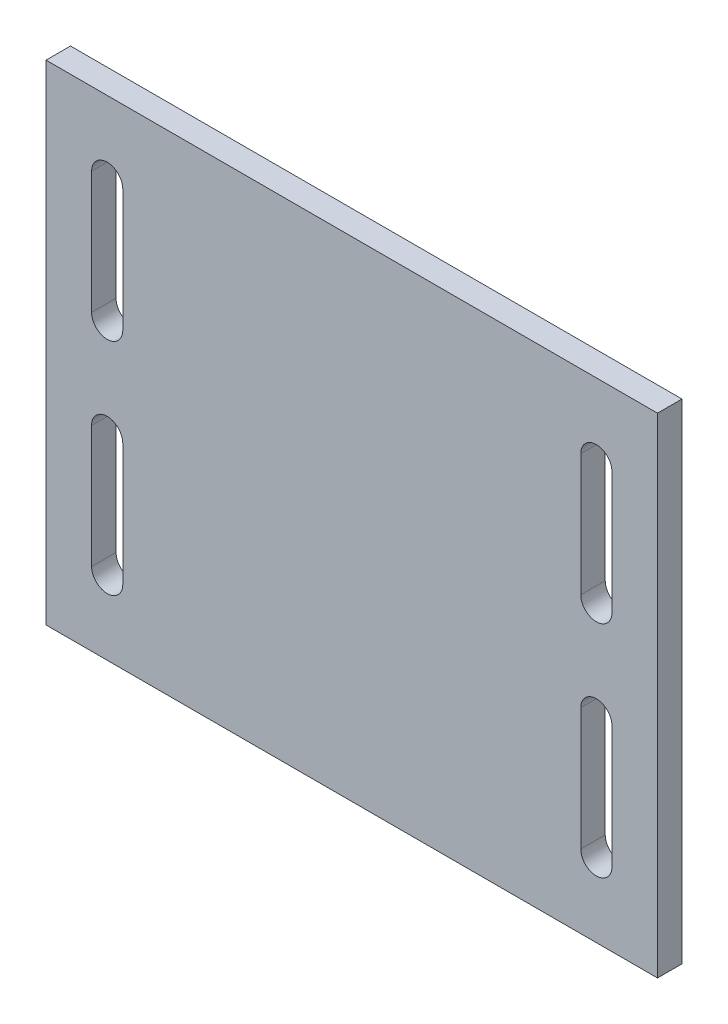
SolidWorks part; units mm, degrees
ref_plane "Front Plane" through (0, 0, 0) normal (0, 0, 1) x (1, 0, 0)
ref_plane "Top Plane" through (0, 0, 0) normal (0, 1, 0) x (1, 0, 0)
ref_plane "Right Plane" through (0, 0, 0) normal (1, 0, 0) x (0, 0, -1)
sketch "Sketch1" plane through (0, 0, 0) normal (0, 0, 1) x (1, 0, 0)
  line L0 (10, 68) -> (10, 48) construction
  line L1 (0, 0) -> (100, 0)
  line L2 (0, 0) -> (0, 80)
  line L3 (0, 80) -> (100, 80)
  line L4 (100, 0) -> (100, 80)
  line L5 (12.55, 68) -> (12.55, 48)
  line L6 (7.45, 68) -> (7.45, 48)
  line L7 (10, 32) -> (10, 12) construction
  line L8 (12.55, 32) -> (12.55, 12)
  line L9 (7.45, 32) -> (7.45, 12)
  line L10 (90, 68) -> (90, 48) construction
  line L11 (92.55, 68) -> (92.55, 48)
  line L12 (87.45, 68) -> (87.45, 48)
  line L13 (90, 32) -> (90, 12) construction
  line L14 (92.55, 32) -> (92.55, 12)
  line L15 (87.45, 32) -> (87.45, 12)
  arc A0 (12.55, 68) -> (7.45, 68) centre (10, 68) ccw
  arc A1 (7.45, 48) -> (12.55, 48) centre (10, 48) ccw
  arc A2 (12.55, 32) -> (7.45, 32) centre (10, 32) ccw
  arc A3 (7.45, 12) -> (12.55, 12) centre (10, 12) ccw
  arc A4 (92.55, 68) -> (87.45, 68) centre (90, 68) ccw
  arc A5 (87.45, 48) -> (92.55, 48) centre (90, 48) ccw
  arc A6 (92.55, 32) -> (87.45, 32) centre (90, 32) ccw
  arc A7 (87.45, 12) -> (92.55, 12) centre (90, 12) ccw
  point P7 (10, 58)
  point P12 (10, 22)
  point P19 (90, 58)
  point P26 (90, 22)
  point P33 (50, 40)
  dimension "D5" = 2.55
  dimension "D6" = 2.55
  dimension "D9" = 2.55
  dimension "D10" = 2.55
  dimension "D1" = 80
  dimension "D2" = 100
  dimension "D3" = 20
  dimension "D4" = 20
  dimension "D7" = 56
  dimension "D8" = 12
  dimension "D11" = 56
  dimension "D12" = 20
  dimension "D13" = 20
  dimension "D14" = 80
  dimension "D15" = 10
  dimension "D16" = 12
extrude "Boss-Extrude1" add sketch "Sketch1" along normal blind 4
